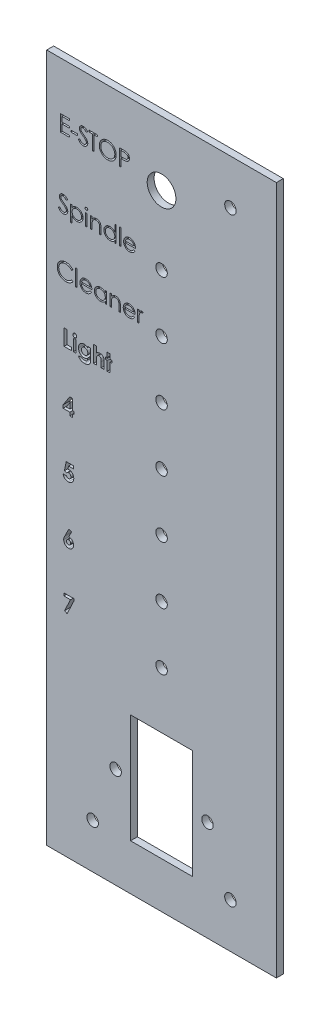
SolidWorks part; units mm, degrees
ref_plane "Front Plane" through (0, 0, 0) normal (0, 0, 1) x (1, 0, 0)
ref_plane "Top Plane" through (0, 0, 0) normal (0, 1, 0) x (1, 0, 0)
ref_plane "Right Plane" through (0, 0, 0) normal (1, 0, 0) x (0, 0, -1)
sketch "Sketch1" plane through (0, 0, 0) normal (0, 0, 1) x (1, 0, 0)
  line L1 (-50, -150) -> (50, -150)
  line L2 (-50, -150) -> (-50, 150)
  line L3 (-50, 150) -> (50, 150)
  line L4 (50, -150) -> (50, 150)
  line L5 (-50, -150) -> (50, 150) construction
  line L6 (-50, 150) -> (50, -150) construction
  point P0 (0, 0)
  dimension "D1" = 300
  dimension "D2" = 100
extrude "Boss-Extrude1" add sketch "Sketch1" along normal blind 3
sketch "Sketch2" plane through (0, 0, 3) normal (0, 0, 1) x (1, 0, 0)
  line L0 (-50, -150) -> (50, -150) construction
  line L5 (-13.5, -130) -> (13.5, -130)
  line L6 (-13.5, -130) -> (-13.5, -82.5)
  line L7 (-13.5, -82.5) -> (13.5, -82.5)
  line L8 (13.5, -130) -> (13.5, -82.5)
  line L9 (0, -1000) -> (0, 49000) construction
  circle A0 centre (20, -106.25) radius 2.5
  circle A1 centre (-20, -106.25) radius 2.5
  point P6 (0, -82.5)
  point P11 (13.5, -106.25)
  dimension "D4" = 20
  dimension "D5" = 5
  dimension "D1" = 47.5
  dimension "D2" = 27
  dimension "D3" = 20
extrude "Cut-Extrude1" cut sketch "Sketch2" against normal up to next
sketch "Sketch3" plane through (0, 0, 3) normal (0, 0, 1) x (1, 0, 0)
  line L0 (0, -1000) -> (0, 49000) construction
  line L1 (50, 150) -> (-50, 150) construction
  line L2 (0, 42) -> (0, 17) construction
  circle A0 centre (0, 122) radius 6.25
  circle A1 centre (0, 92) radius 2.5
  circle A2 centre (0, 67) radius 2.5
  circle A3 centre (0, 42) radius 2.5
  circle A4 centre (0, 17) radius 2.5
  circle A5 centre (0, -8) radius 2.5
  circle A6 centre (0, -33) radius 2.5
  circle A7 centre (0, -58) radius 2.5
  dimension "D1" = 12.5
  dimension "D3" = 5
  dimension "D5" = 25
  dimension "D6" = 25
  dimension "D2" = 28
  dimension "D4" = 30
  dimension "D8" = 25
  dimension "D7" = 5
extrude "Cut-Extrude2" cut sketch "Sketch3" against normal through all
sketch "Sketch4" plane through (0, 0, 3) normal (0, 0, 1) x (1, 0, 0)
  line L0 (0, 122) -> (-50, 122) construction
  line L1 (-50, 150) -> (-50, -150) construction
  line L2 (0, 92) -> (-50, 92) construction
  line L3 (0, 67) -> (-50, 67) construction
  line L4 (0, 42) -> (-50, 42) construction
  line L5 (0, 17) -> (-50, 17) construction
  line L6 (0, -8) -> (-50, -8) construction
  line L7 (0, -33) -> (-50, -33) construction
  line L8 (0, -58) -> (-50, -58) construction
  text T0 "E-STOP     " font "Century Gothic" height 7
  text T1 "Spindle    " font "Century Gothic" height 7
  text T2 "Cleaner   " font "Century Gothic" height 7
  text T3 "<b>Light        </b>" font "Century Gothic" height 7
  text T4 "<b>4</b>              " font "Century Gothic" height 7
  text T5 "<b>5              </b>" font "Century Gothic" height 7
  text T6 "<b>6              </b>" font "Century Gothic" height 7
  text T7 "<b>7              </b>" font "Century Gothic" height 7
  dimension "D2" = 25
  dimension "D1" = 5
extrude "Cut-Extrude3" cut sketch "Sketch4" against normal through all
sketch "Sketch5" plane through (0, 0, 3) normal (0, 0, 1) x (1, 0, 0)
  line L0 (0, -1000) -> (0, 49000) construction
  line L1 (-1000, 0) -> (49000, 0) construction
  line L2 (-50, -150) -> (50, -150) construction
  line L3 (-50, 150) -> (-50, -150) construction
  circle A0 centre (-30, -130.5) radius 2.5
  circle A1 centre (30, -130.5) radius 2.5
  circle A2 centre (30, 130.5) radius 2.5
  dimension "D3" = 5
  dimension "D1" = 19.5
  dimension "D2" = 20
extrude "Cut-Extrude4" cut sketch "Sketch5" against normal through all
